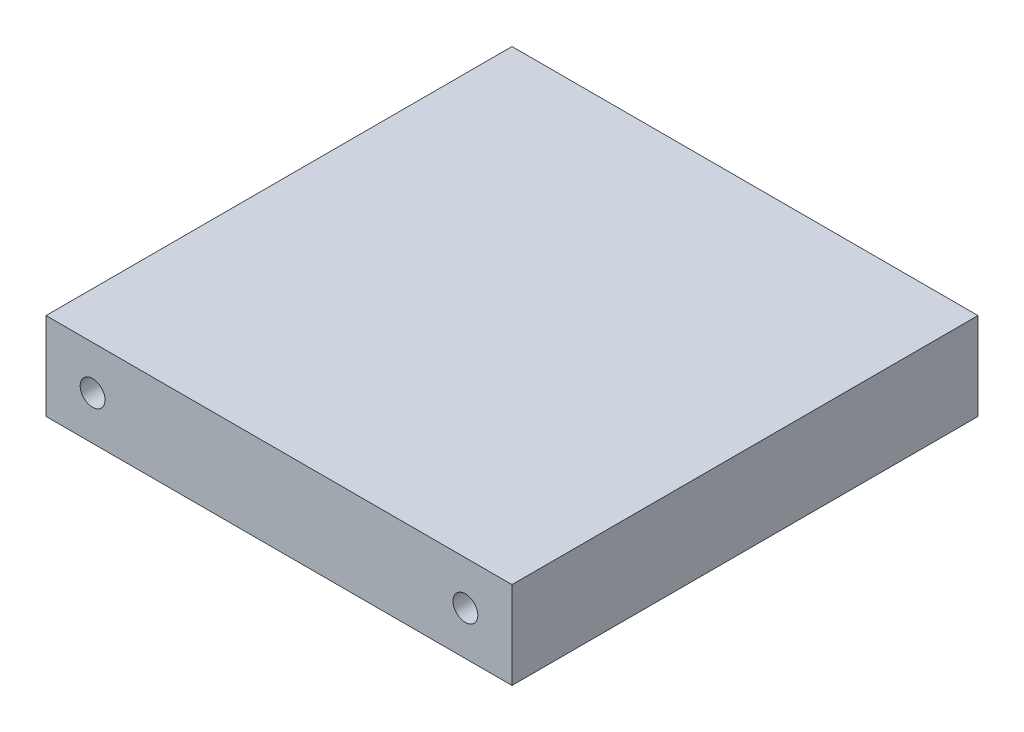
SolidWorks part; units mm, degrees
ref_plane "Front Plane" through (0, 0, 0) normal (0, 0, 1) x (1, 0, 0)
ref_plane "Top Plane" through (0, 0, 0) normal (0, 1, 0) x (1, 0, 0)
ref_plane "Right Plane" through (0, 0, 0) normal (1, 0, 0) x (0, 0, -1)
sketch "Sketch2" plane through (0, 0, 0) normal (0, 1, 0) x (1, 0, 0)
  line L1 (-25.4, 25.4) -> (25.4, 25.4)
  line L2 (-25.4, 25.4) -> (-25.4, -25.4)
  line L3 (-25.4, -25.4) -> (25.4, -25.4)
  line L4 (25.4, 25.4) -> (25.4, -25.4)
  line L5 (-25.4, 25.4) -> (25.4, -25.4) construction
  line L6 (-25.4, -25.4) -> (25.4, 25.4) construction
  point P0 (0, 0)
  dimension "D1" = 50.8
  dimension "D2" = 50.8
extrude "Boss-Extrude1" add sketch "Sketch2" along normal blind 9.525 contours L2 L3 L4 L1
sketch "Sketch3" plane through (0, 0, 25.4) normal (0, 0, 1) x (1, 0, 0)
  line L0 (25.4, 9.525) -> (25.4, 0) construction
  line L1 (-25.4, 9.525) -> (-25.4, 0) construction
  circle A0 centre (20.32, 4.7625) radius 1.8415
  circle A1 centre (-20.32, 4.7625) radius 1.8415
  point P7 (25.4, 4.7625)
  dimension "D1" = 5.08
  dimension "D2" = 5.08
hole_wizard "#6-32 Tapped Hole1" positions "Sketch4" profile "Sketch5" tap size "#6-32" standard "ANSI Inch"
sketch "Sketch4" plane through (0, 0, 25.4) normal (0, 0, 1) x (1, 0, 0)
  circle A0 centre (-20.32, 4.7625) radius 1.8415 construction
  circle A1 centre (20.32, 4.7625) radius 1.8415 construction
  point P0 (-20.32, 4.7625)
  point P2 (20.32, 4.7625)
sketch "Sketch5" plane through (-20.32, 4.7625, 25.4) normal (1, 0, 0) x (0, -1, 0)
  line L0 (0, 0) -> (0, 10.2107)
  line L1 (0, 10.2107) -> (1.3525, 9.398)
  line L2 (1.3525, 9.398) -> (1.3525, 0)
  line L5 (1.3525, 0) -> (0, 0)
  line L10 (0, 10.2107) -> (-1.3526, 9.398) construction
  line L11 (0, -6.35) -> (0, 107.95) construction
  dimension "Tap Drill Dia." = 2.7051
  dimension "Tap Drill Depth" = 9.398
  dimension "Drill Angle" = 118
cosmetic thread "Hole Thread1" parameters "D1"=7.112, "D2"=3.5052
cosmetic thread "Hole Thread2" parameters "D1"=7.112, "D2"=3.5052
hole_wizard "#6-32 Tapped Hole2" positions "Sketch6" profile "Sketch7" tap size "#6-32" standard "ANSI Inch"
sketch "Sketch6" plane through (0, 0, -25.4) normal (0, 0, -1) x (-1, 0, 0)
  circle A0 centre (-20.32, 4.7625) radius 1.8415 construction
  circle A1 centre (20.32, 4.7625) radius 1.8415 construction
  point P0 (-20.32, 4.7625)
  point P2 (20.32, 4.7625)
sketch "Sketch7" plane through (20.32, 4.7625, -25.4) normal (1, 0, 0) x (0, 1, 0)
  line L0 (0, 0) -> (0, 10.2107)
  line L1 (0, 10.2107) -> (1.3525, 9.398)
  line L2 (1.3525, 9.398) -> (1.3525, 0)
  line L5 (1.3525, 0) -> (0, 0)
  line L10 (0, 10.2107) -> (-1.3525, 9.398) construction
  line L11 (0, -6.35) -> (0, 107.95) construction
  dimension "Tap Drill Dia." = 2.7051
  dimension "Tap Drill Depth" = 9.398
  dimension "Drill Angle" = 118
cosmetic thread "Hole Thread3" parameters "D1"=7.112, "D2"=3.5052
cosmetic thread "Hole Thread4" parameters "D1"=7.112, "D2"=3.5052
